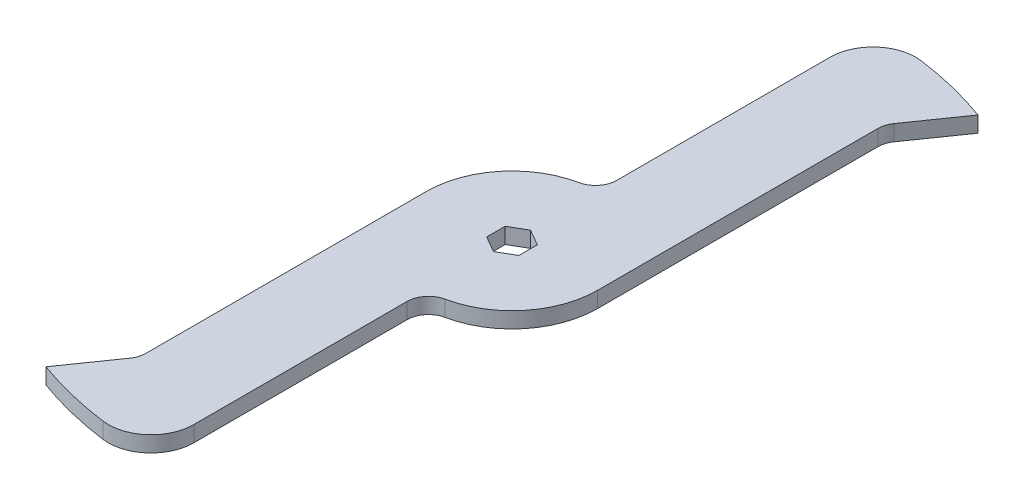
SolidWorks part; units mm, degrees
material "Plain Carbon Steel"
ref_plane "Front Plane" through (0, 0, 0) normal (0, 0, 1) x (1, 0, 0)
ref_plane "Top Plane" through (0, 0, 0) normal (0, 1, 0) x (1, 0, 0)
ref_plane "Right Plane" through (0, 0, 0) normal (1, 0, 0) x (0, 0, -1)
sketch "Sketch1" plane through (0, 0, 0) normal (0, 1, 0) x (1, 0, 0)
  line L0 (0, 25.4) -> (0, 107.95)
  line L1 (25.4, 0) -> (25.4, 85.1942)
  line L2 (25.4, 85.1942) -> (36.7775, 101.492)
  line L3 (36.7775, 101.492) -> (0, 0) construction
  line L4 (0, -25.4) -> (0, -107.95)
  line L5 (-25.4, -85.1942) -> (-36.7775, -101.492)
  line L6 (-25.4, 0) -> (-25.4, -85.1942)
  circle A0 centre (0, 0) radius 107.95 construction
  circle A2 centre (0, 0) radius 25.4 construction
  arc A3 (0, 107.95) -> (36.7775, 101.492) centre (0, 0) cw
  circle A4 centre (0, 0) radius 88.9 construction
  arc A5 (0, -107.95) -> (-36.7775, -101.492) centre (0, 0) cw
  arc A6 (0, 25.4) -> (-25.4, 0) centre (0, 0) ccw
  arc A7 (25.4, 0) -> (0, -25.4) centre (0, 0) cw
  point P18 (0, 0)
  dimension "D1" = 215.9
  dimension "D2" = 50.8
  dimension "D3" = 15
  dimension "D4" = 177.8
  dimension "D5" = 2
extrude "Boss-Extrude1" add sketch "Sketch1" along normal blind 4.699
sketch "Sketch2" plane through (0, 4.699, 0) normal (0, 1, 0) x (1, 0, 0)
  line L1 (0, 5.4993) -> (-4.7625, 2.7496)
  line L2 (-4.7625, 2.7496) -> (-4.7625, -2.7496)
  line L3 (-4.7625, -2.7496) -> (0, -5.4993)
  line L4 (0, -5.4993) -> (4.7625, -2.7496)
  line L5 (4.7625, -2.7496) -> (4.7625, 2.7496)
  line L6 (4.7625, 2.7496) -> (0, 5.4993)
  circle A0 centre (0, 0) radius 4.7625 construction
  dimension "D1" = 9.525
extrude "Cut-Extrude1" cut sketch "Sketch2" against normal up to next
fillet "Fillet1" radius 6.35 4 edges at (-25.4, 2.3495, 85.1942) (0, 2.3495, 25.4) (25.4, 2.3495, -85.1942) (0, 2.3495, -25.4)
fillet "Fillet2" radius 12.7 2 edges at (0, 2.3495, -107.95) (0, 2.3495, 107.95)
